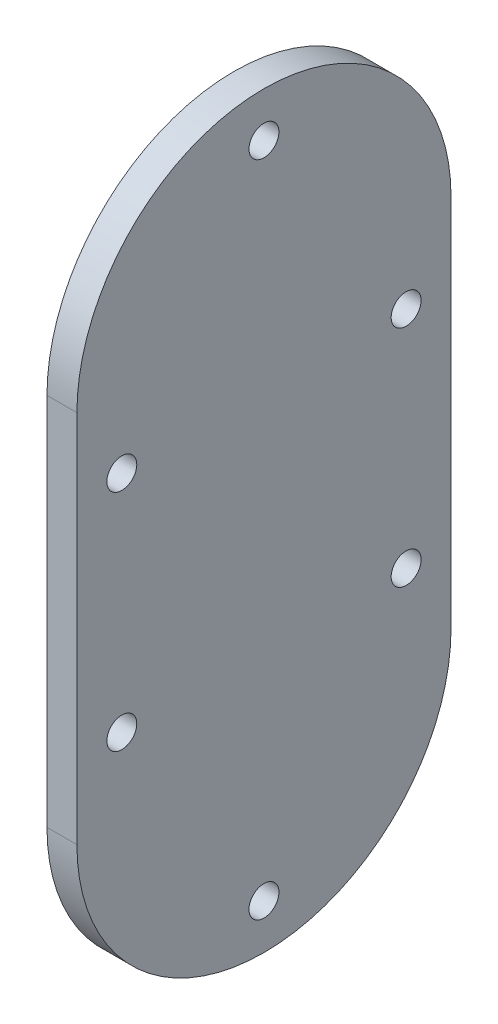
SolidWorks part; units mm, degrees
material "Acrylic (Medium-high impact)"
ref_plane "Front Plane" through (0, 0, 0) normal (1, 0, 0) x (0, 1, 0)
ref_plane "Top Plane" through (0, 0, 0) normal (0, 0, 1) x (0, 1, 0)
ref_plane "Right Plane" through (0, 0, 0) normal (0, 1, 0) x (-1, 0, 0)
sketch "Sketch1" plane through (0, 0, 0) normal (1, 0, 0) x (0, 1, 0)
  line L0 (0, 0) -> (50, 0) construction
  line L1 (0, 25) -> (50, 25)
  line L2 (0, -25) -> (50, -25)
  arc A0 (0, 25) -> (0, -25) centre (0, 0) ccw
  arc A1 (50, -25) -> (50, 25) centre (50, 0) ccw
  circle A2 centre (10, 19) radius 2
  circle A3 centre (40, 19) radius 2
  circle A4 centre (69, 0) radius 2
  circle A5 centre (-19, 0) radius 2
  circle A6 centre (10, -19) radius 2
  circle A7 centre (40, -19) radius 2
  point P3 (25, 0)
  point P20 (0, 0)
  point P21 (75, 0)
  point P22 (-25, 0)
  dimension "D2" = 25
  dimension "D3" = 4
  dimension "D1" = 50
  dimension "D4" = 6
  dimension "D5" = 6
  dimension "D6" = 6
  dimension "D7" = 6
  dimension "D8" = 10
  dimension "D9" = 10
  dimension "D10" = 25
  dimension "D11" = 6
extrude "Boss-Extrude1" add sketch "Sketch1" along normal blind 4
